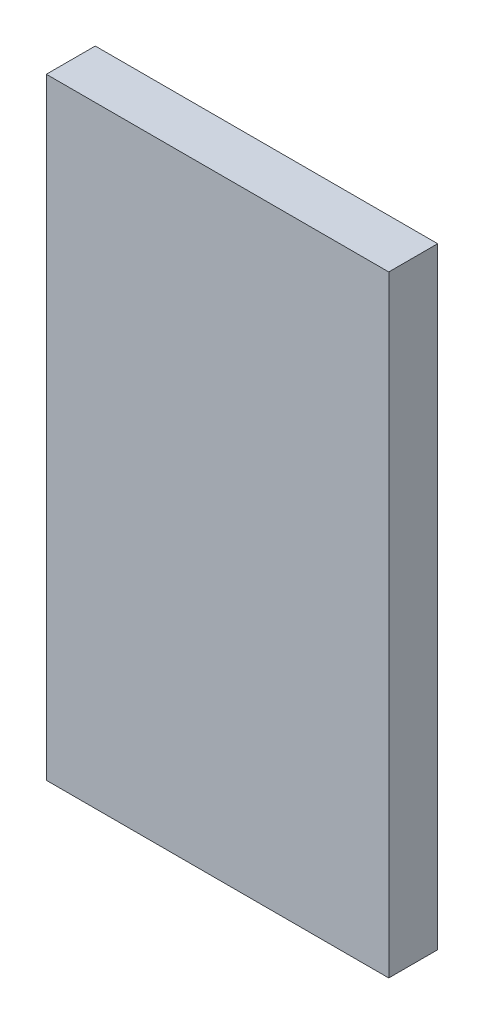
SolidWorks part; units mm, degrees
ref_plane "Front Plane" through (0, 0, 0) normal (0, 0, 1) x (1, 0, 0)
ref_plane "Top Plane" through (0, 0, 0) normal (0, 1, 0) x (1, 0, 0)
ref_plane "Right Plane" through (0, 0, 0) normal (1, 0, 0) x (0, 0, -1)
sketch "Sketch2" plane through (0, 0, 0) normal (0, 0, 1) x (1, 0, 0)
  line L1 (-70, -125) -> (70, -125)
  line L2 (-70, -125) -> (-70, 125)
  line L3 (-70, 125) -> (70, 125)
  line L4 (70, -125) -> (70, 125)
  line L5 (-70, -125) -> (70, 125) construction
  line L6 (-70, 125) -> (70, -125) construction
  point P0 (0, 0)
  dimension "D1" = 140
  dimension "D2" = 250
extrude "Boss-Extrude1" add sketch "Sketch2" along normal blind 20
